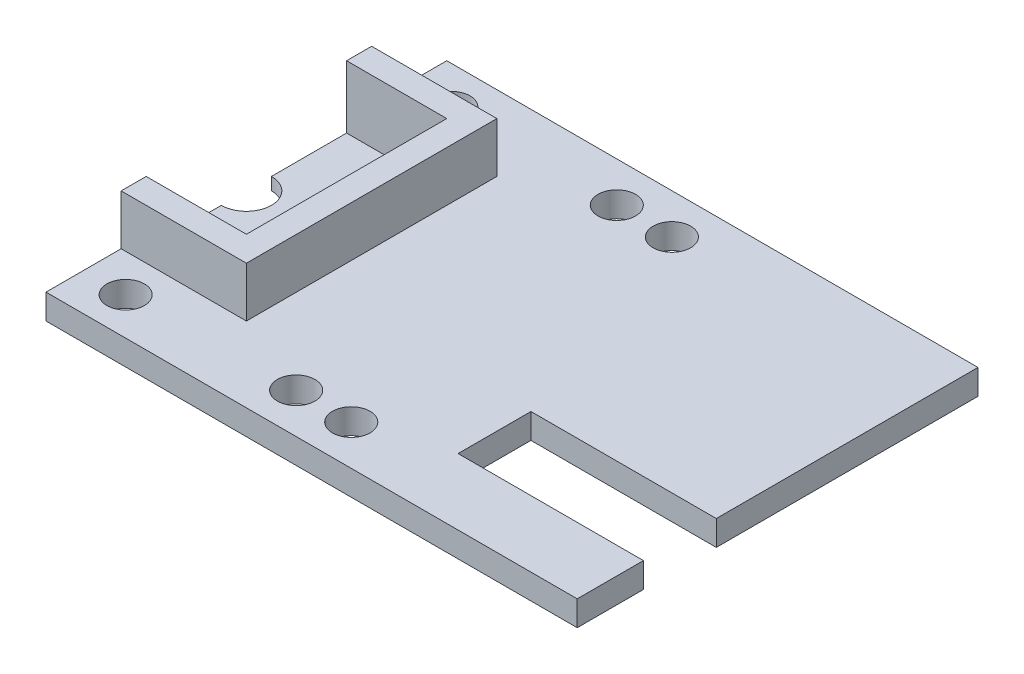
SolidWorks part; units mm, degrees
ref_plane "Front Plane" through (0, 0, 0) normal (0, 0, 1) x (1, 0, 0)
ref_plane "Top Plane" through (0, 0, 0) normal (0, 1, 0) x (1, 0, 0)
ref_plane "Right Plane" through (0, 0, 0) normal (1, 0, 0) x (0, 0, -1)
sketch "Sketch1" plane through (0, 0, 0) normal (0, 1, 0) x (1, 0, 0)
  line L1 (-279.4, -50.8) -> (0, -50.8)
  line L2 (-279.4, -50.8) -> (-279.4, 50.8)
  line L3 (-279.4, 50.8) -> (0, 50.8)
  line L4 (0, -50.8) -> (0, 50.8)
  point P0 (0, 0)
  dimension "D1" = 279.4
  dimension "D2" = 101.6
extrude "Boss-Extrude1" add sketch "Sketch1" along normal blind 6.35
sketch "Sketch2" plane through (0, 6.35, 0) normal (0, 1, 0) x (1, 0, 0)
  line L0 (-279.4, 50.8) -> (-279.4, -50.8) construction
  line L2 (0, 50.8) -> (-279.4, 50.8) construction
  circle A0 centre (-258.5106, 0) radius 13.97
  dimension "D1" = 50.8
  dimension "D2" = 27.94
  dimension "D3" = 20.8894
extrude "Boss-Extrude3" add sketch "Sketch2" along normal blind 5.5562
sketch "Sketch9" plane through (0, 11.9062, 0) normal (0, 1, 0) x (1, 0, 0)
  circle A0 centre (-258.5106, 0) radius 11.1125
extrude "Cut-Extrude4" cut sketch "Sketch9" against normal blind 4.445
sketch "Sketch10" plane through (0, 0, 0) normal (0, -1, 0) x (-1, 0, 0)
  circle A0 centre (258.5106, 0) radius 11.1125
extrude "Cut-Extrude5" cut sketch "Sketch10" against normal blind 5.5562
sketch "Sketch11" plane through (0, 7.4613, 0) normal (0, 1, 0) x (1, 0, 0)
  circle A0 centre (-258.5106, 0) radius 7.9375
extrude "Cut-Extrude6" cut sketch "Sketch11" against normal through all
sketch "Sketch12" plane through (0, 6.35, 0) normal (0, 1, 0) x (1, 0, 0)
  line L0 (0, 50.8) -> (-279.4, 50.8) construction
  line L1 (-279.4, 50.8) -> (-279.4, -50.8) construction
  circle A0 centre (-134.6662, 0) radius 6.35
  dimension "D1" = 12.7
  dimension "D2" = 50.8
  dimension "D3" = 144.7338
extrude "Cut-Extrude7" cut sketch "Sketch12" against normal through all
sketch "Sketch22" plane through (0, 6.35, 0) normal (0, 1, 0) x (1, 0, 0)
  line L1 (-102.9162, -31.75) -> (-166.4162, -31.75)
  line L2 (-102.9162, -31.75) -> (-102.9162, 31.75)
  line L3 (-102.9162, 31.75) -> (-166.4162, 31.75)
  line L4 (-166.4162, -31.75) -> (-166.4162, 31.75)
  line L5 (-102.9162, -31.75) -> (-166.4162, 31.75) construction
  line L6 (-102.9162, 31.75) -> (-166.4162, -31.75) construction
  circle A0 centre (-134.6662, 0) radius 6.35 construction
  point P0 (-134.6662, 0)
extrude "Boss-Extrude7" add sketch "Sketch22" along normal blind 12.7
sketch "Sketch25" plane through (0, 19.05, 0) normal (0, 1, 0) x (1, 0, 0)
  line L1 (-109.2662, -25.4) -> (-160.0662, -25.4)
  line L2 (-109.2662, -25.4) -> (-109.2662, 25.4)
  line L3 (-109.2662, 25.4) -> (-160.0662, 25.4)
  line L4 (-160.0662, -25.4) -> (-160.0662, 25.4)
  line L5 (-109.2662, -25.4) -> (-160.0662, 25.4) construction
  line L6 (-109.2662, 25.4) -> (-160.0662, -25.4) construction
  circle A0 centre (-134.6662, 0) radius 6.35 construction
  point P0 (-134.6662, 0)
  dimension "D1" = 50.8
  dimension "D2" = 50.8
extrude "Cut-Extrude11" cut sketch "Sketch25" against normal blind 15.875
sketch "Sketch32" plane through (0, 6.35, 0) normal (0, 1, 0) x (1, 0, 0)
  line L3 (-279.4, -50.8) -> (0, -50.8) construction
  line L5 (0, 50.8) -> (-279.4, 50.8) construction
  circle A0 centre (-67.442, -40.64) radius 4.7625
  circle A1 centre (-81.412, -40.64) radius 4.7625
  circle A2 centre (-67.442, 40.64) radius 4.7625
  circle A3 centre (-81.412, 40.64) radius 4.7625
  dimension "D1" = 10.16
  dimension "D2" = 10.16
  dimension "D3" = 10.16
  dimension "D4" = 10.16
  dimension "D5" = 13.97
  dimension "D6" = 13.97
  dimension "D7" = 81.28
extrude "Cut-Extrude12" cut sketch "Sketch32" against normal blind 6.35
sketch "Sketch38" plane through (0, 6.35, 0) normal (0, 1, 0) x (1, 0, 0)
  line L0 (0, -50.8) -> (0, 50.8) construction
  line L1 (0, -34.0128) -> (-46.99, -34.0128)
  line L2 (0, -34.0128) -> (0, -15.5426)
  line L3 (0, -15.5426) -> (-46.99, -15.5426)
  line L4 (-46.99, -34.0128) -> (-46.99, -15.5426)
  line L6 (-279.4, -50.8) -> (0, -50.8) construction
  dimension "D1" = 35.2574
  dimension "D2" = 18.4703
  dimension "D3" = 46.99
extrude "Cut-Extrude13" cut sketch "Sketch38" against normal blind 6.35
sketch "Sketch60" plane through (0, 6.35, 0) normal (0, 1, 0) x (1, 0, 0)
  line L1 (-279.4, 50.8) -> (-279.4, -50.8) construction
  line L2 (0, 50.8) -> (-279.4, 50.8) construction
  circle A0 centre (-231.7492, 41.3241) radius 4.7625
  circle A1 centre (-231.7492, -39.3693) radius 4.7625
  circle A2 centre (-173.5092, -39.3693) radius 4.7625
  circle A3 centre (-173.5092, 41.3241) radius 4.7625
  dimension "D1" = 47.6508
  dimension "D5" = 9.525
  dimension "D6" = 9.525
  dimension "D7" = 9.525
  dimension "D8" = 9.525
  dimension "D2" = 58.24
  dimension "D3" = 80.6935
  dimension "D4" = 9.4759
  dimension "D9" = 105.8908
extrude "Cut-Extrude23" cut sketch "Sketch60" against normal up to surface (6.35 mm away) up to face at (-81.5975, 0, 12.3889)
sketch "Sketch62" plane through (0, 6.35, 0) normal (0, 1, 0) x (1, 0, 0)
  line L0 (-134.6662, 0) -> (-134.6662, 50.8)
  line L1 (0, 50.8) -> (-279.4, 50.8) construction
  line L2 (-134.6662, 0) -> (-134.6662, -50.8)
  line L3 (-279.4, -50.8) -> (0, -50.8) construction
extrude "Cut-Extrude26" cut sketch "Sketch62" against normal through all and the other way through all flip side to cut
sketch "Sketch63" plane through (0, 6.35, 0) normal (0, 1, 0) x (1, 0, 0)
  line L0 (0, 50.8) -> (-134.6662, 50.8) construction
  line L1 (-134.6662, 50.8) -> (-134.6662, 31.75) construction
  circle A0 centre (-123.9982, 41.275) radius 4.7625
  point P2 (-123.6355, 41.5058)
  dimension "D1" = 9.525
  dimension "D2" = 9.525
  dimension "D3" = 10.668
extrude "Cut-Extrude27" cut sketch "Sketch63" against normal through all
mirror "Mirror1" about plane through (0, 0, 0) normal (0, 0, 1) of "Cut-Extrude27"
